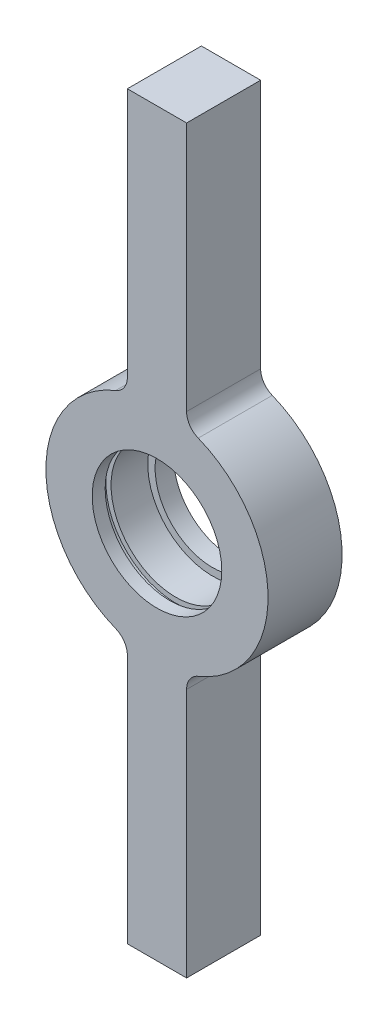
SolidWorks part; units mm, degrees
ref_plane "Front Plane" through (0, 0, 0) normal (0, 0, 1) x (1, 0, 0)
ref_plane "Top Plane" through (0, 0, 0) normal (0, 1, 0) x (1, 0, 0)
ref_plane "Right Plane" through (0, 0, 0) normal (1, 0, 0) x (0, 0, -1)
sketch "Sketch1" plane through (0, 0, 0) normal (0, 0, 1) x (1, 0, 0)
  circle A0 centre (0, 0) radius 15.5
  circle A1 centre (0, 0) radius 30
  dimension "D1" = 31
  dimension "D2" = 60
extrude "Boss-Extrude1" add sketch "Sketch1" along normal mid plane 20
sketch "Sketch2" plane through (0, 0, 0) normal (0, 0, 1) x (1, 0, 0)
  line L0 (0, 0) -> (0, 74.602) construction
  line L1 (-8, 100) -> (8, 100)
  line L2 (8, 100) -> (8, 28.9137)
  line L3 (8, 28.9137) -> (0, 30)
  line L4 (-8, 28.9137) -> (0, 30)
  line L5 (-8, 100) -> (-8, 28.9137)
  circle A0 centre (0, 0) radius 30 construction
  point P11 (0, 100)
  dimension "D1" = 16
  dimension "D2" = 100
extrude "Boss-Extrude2" add sketch "Sketch2" along normal mid plane 20
mirror "Mirror1" about plane through (0, 0, 0) normal (0, 1, 0) of "Boss-Extrude2"
sketch "Sketch3" plane through (0, 0, 0) normal (1, 0, 0) x (0, 0, -1)
  line L0 (0, 0) -> (53.684, 0) construction
  line L1 (5, 15.5) -> (5, 17.5)
  line L2 (10, 15.5) -> (-10, 15.5) construction
  line L3 (5, 17.5) -> (-10, 17.5)
  line L4 (-10, 28.9137) -> (-10, -28.9137) construction
  line L5 (-10, 17.5) -> (-10, 15.5)
  line L6 (-10, 15.5) -> (5, 15.5)
  dimension "D1" = 17.5
  dimension "D2" = 15
revolve "Cut-Revolve1" cut sketch "Sketch3" angle 360 about L0
sketch "Sketch4" plane through (0, 0, 0) normal (1, 0, 0) x (0, 0, -1)
  line L0 (0, 0) -> (21.5903, 0) construction
  line L1 (-4.9, 17) -> (-4.9, 18.9)
  line L2 (-4.9, 18.9) -> (-6.5, 18.9)
  line L3 (-6.5, 18.9) -> (-6.5, 17)
  line L4 (-6.5, 17) -> (-4.9, 17)
  line L5 (5, 17.5) -> (5, -17.5) construction
  dimension "D1" = 11.5
  dimension "D2" = 1.6
  dimension "D3" = 18.9
  dimension "D4" = 17
revolve "Cut-Revolve2" cut sketch "Sketch4" angle 360 about L0
fillet "Fillet1" radius 5 4 edges at (8, -28.9137, 0) (-8, -28.9137, 0) (-8, 28.9137, 0) (8, 28.9137, 0)
